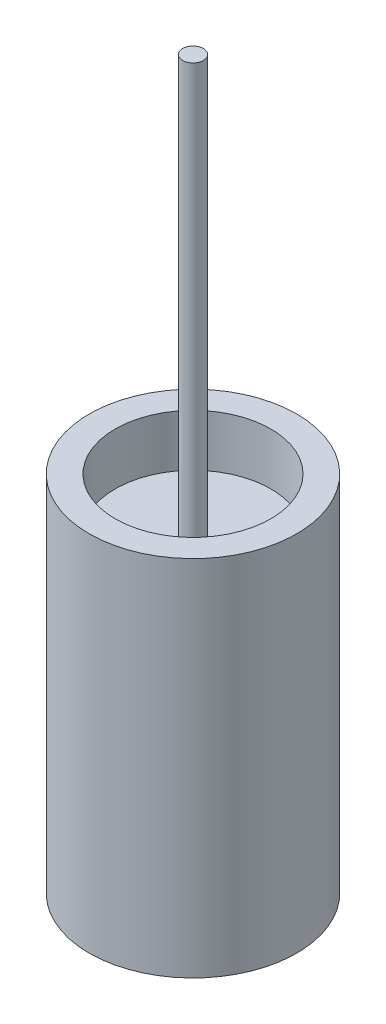
SolidWorks part; units mm, degrees
ref_plane "Front Plane" through (0, 0, 0) normal (0, 0, 1) x (1, 0, 0)
ref_plane "Top Plane" through (0, 0, 0) normal (0, 1, 0) x (1, 0, 0)
ref_plane "Right Plane" through (0, 0, 0) normal (1, 0, 0) x (0, 0, -1)
sketch "Sketch1" plane through (0, 0, 0) normal (0, 1, 0) x (1, 0, 0)
  circle A0 centre (0, 0) radius 10
extrude "Boss-Extrude2" add sketch "Sketch1" along normal blind 35
shell "Shell1" thickness 2.5
ref_point "Point1"
sketch "Sketch2" plane through (0, 30, 0) normal (0, 1, 0) x (1, 0, 0)
  circle A0 centre (0, 0) radius 1
  dimension "D1" = 2
extrude "Boss-Extrude3" add sketch "Sketch2" along normal blind 40
